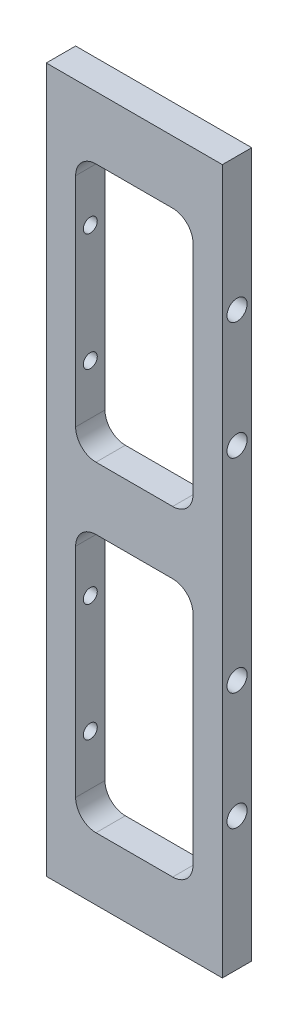
SolidWorks part; units mm, degrees
material "6061-T6 (SS)"
ref_plane "Front Plane" through (0, 0, 0) normal (0, 0, 1) x (1, 0, 0)
ref_plane "Top Plane" through (0, 0, 0) normal (0, 1, 0) x (1, 0, 0)
ref_plane "Right Plane" through (0, 0, 0) normal (1, 0, 0) x (0, 0, -1)
sketch "Sketch1" plane through (0, 0, 0) normal (0, 0, 1) x (1, 0, 0)
  line L1 (-14.2875, -57.15) -> (14.2875, -57.15)
  line L2 (-14.2875, -57.15) -> (-14.2875, 57.15)
  line L3 (-14.2875, 57.15) -> (14.2875, 57.15)
  line L4 (14.2875, -57.15) -> (14.2875, 57.15)
  line L5 (-14.2875, -57.15) -> (14.2875, 57.15) construction
  line L6 (-14.2875, 57.15) -> (14.2875, -57.15) construction
  point P0 (0, 0)
  dimension "D1" = 28.575
  dimension "D2" = 114.3
extrude "Boss-Extrude1" add sketch "Sketch1" along normal blind 4.7625
sketch "Sketch2" plane through (0, 0, 4.7625) normal (0, 0, 1) x (1, 0, 0)
  line L0 (-14.2875, 0) -> (14.2875, 0) construction
  line L1 (-14.2875, 57.15) -> (-14.2875, -57.15) construction
  line L2 (14.2875, -57.15) -> (14.2875, 57.15) construction
  line L3 (0, 57.15) -> (0, 0) construction
  line L4 (14.2875, 57.15) -> (-14.2875, 57.15) construction
  line L5 (-9.525, -46.99) -> (9.525, -5.08) construction
  line L6 (-9.525, 5.08) -> (9.525, 5.08)
  line L7 (-9.525, 5.08) -> (-9.525, 46.99)
  line L8 (-9.525, 46.99) -> (9.525, 46.99)
  line L9 (9.525, 5.08) -> (9.525, 46.99)
  line L10 (-9.525, 5.08) -> (9.525, 46.99) construction
  line L11 (-9.525, 46.99) -> (9.525, 5.08) construction
  line L12 (-9.525, -5.08) -> (9.525, -46.99) construction
  line L13 (9.525, -5.08) -> (9.525, -46.99)
  line L14 (-9.525, -46.99) -> (9.525, -46.99)
  line L15 (-9.525, -5.08) -> (-9.525, -46.99)
  line L16 (-9.525, -5.08) -> (9.525, -5.08)
  point P11 (0, 26.035)
  point P20 (0, -26.035)
  dimension "D1" = 4.7625
  dimension "D2" = 5.08
  dimension "D3" = 10.16
extrude "Cut-Extrude1" cut sketch "Sketch2" against normal through all
fillet "Fillet1" radius 3.302 8 edges at (-9.525, -46.99, 2.3813) (9.525, -46.99, 2.3813) (-9.525, -5.08, 2.3813) (9.525, -5.08, 2.3813) (-9.525, 5.08, 2.3813) (9.525, 5.08, 2.3813) (9.525, 46.99, 2.3813) (-9.525, 46.99, 2.3813)
hole_wizard "#4 Clearance Hole1" positions "Sketch4" profile "Sketch5" hole size "#4" standard "ANSI Inch"
sketch "Sketch4" plane through (14.2875, 0, 0) normal (1, 0, 0) x (0, 0, -1)
  line L0 (-2.3813, 57.15) -> (-2.3813, -57.15) construction
  line L1 (-4.7625, 57.15) -> (0, 57.15) construction
  line L2 (-4.7625, -57.15) -> (0, -57.15) construction
  line L3 (0, -57.15) -> (0, 57.15) construction
  point P9 (-2.3812, 35.56)
  point P23 (-2.3812, 16.51)
  point P29 (-2.3812, -16.51)
  point P31 (-2.3812, -35.56)
  point P44 (0, 0)
  dimension "D1" = 19.05
  dimension "D2" = 16.51
  dimension "D3" = 16.51
  dimension "D4" = 19.05
sketch "Sketch5" plane through (14.2875, 35.56, 2.3812) normal (0, 1, 0) x (0, 0, -1)
  line L0 (0, 0) -> (0, 4.7625)
  line L1 (0, 4.7625) -> (1.6319, 4.7625)
  line L2 (1.6319, 4.7625) -> (1.6319, 0)
  line L5 (1.6319, 0) -> (0, 0)
  line L11 (0, -6.35) -> (0, 107.95) construction
  dimension "Thru Hole Dia." = 3.2639
  dimension "Thru Hole Depth" = 4.7625
hole_wizard "#4-40 Tapped Hole1" positions "Sketch7" profile "Sketch6" tap size "#4-40" standard "ANSI Inch" end condition up to next
sketch "Sketch7" plane through (-14.2875, 0, 0) normal (-1, 0, 0) x (0, 0, 1)
  line L0 (2.3813, 57.15) -> (2.3813, -57.15) construction
  line L1 (4.7625, 57.15) -> (0, 57.15) construction
  line L2 (4.7625, -57.15) -> (0, -57.15) construction
  line L4 (0, 0) -> (4.7625, 0) construction
  line L5 (0, 57.15) -> (0, -57.15) construction
  line L6 (4.7625, 57.15) -> (4.7625, -57.15) construction
  point P17 (2.3812, 16.51)
  point P19 (2.3812, 35.56)
  point P21 (2.3812, -16.51)
  point P23 (2.3812, -35.56)
  dimension "D1" = 16.51
  dimension "D2" = 19.05
  dimension "D3" = 16.51
  dimension "D4" = 19.05
sketch "Sketch6" plane through (-14.2875, 16.51, 2.3812) normal (0, 1, 0) x (0, 0, 1)
  line L0 (0, 0) -> (0, 4.7625)
  line L1 (0, 4.7625) -> (1.1303, 4.7625)
  line L2 (1.1303, 4.7625) -> (1.1303, 0)
  line L5 (1.1303, 0) -> (0, 0)
  line L11 (0, -6.35) -> (0, 107.95) construction
  dimension "Thru Tap Drill Dia." = 2.2606
  dimension "Thru Tap Drill Depth" = 4.7625
cosmetic thread "Hole Thread1" parameters "D2"=2.8448
cosmetic thread "Hole Thread2" parameters "D2"=2.8448
cosmetic thread "Hole Thread3" parameters "D2"=2.8448
cosmetic thread "Hole Thread4" parameters "D2"=2.8448
